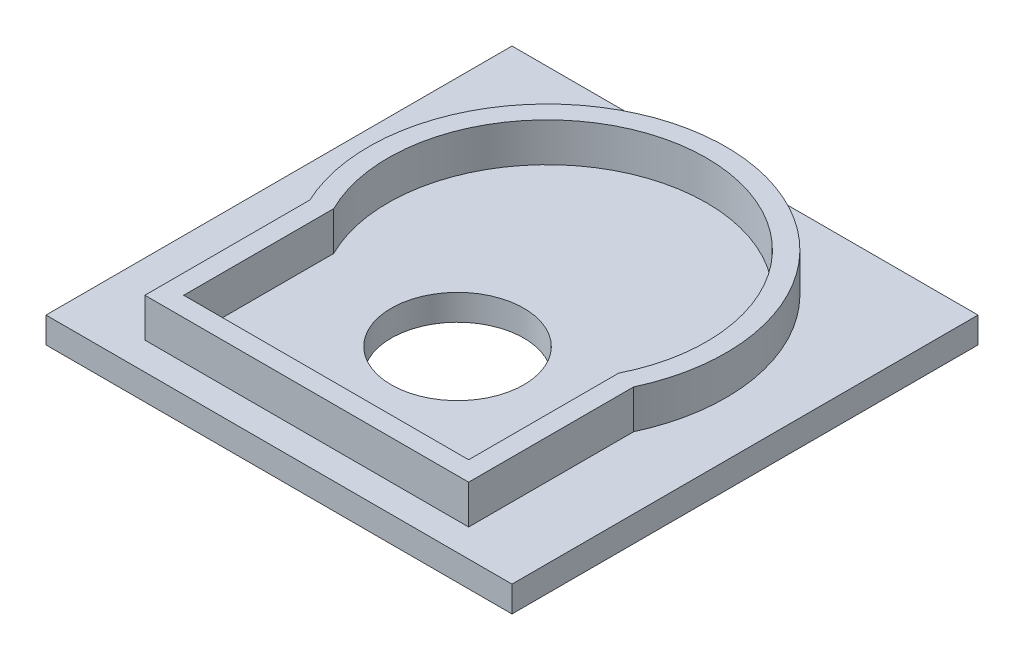
SolidWorks part; units mm, degrees
ref_plane "Front Plane" through (0, 0, 0) normal (0, 0, 1) x (1, 0, 0)
ref_plane "Top Plane" through (0, 0, 0) normal (0, 1, 0) x (1, 0, 0)
ref_plane "Right Plane" through (0, 0, 0) normal (1, 0, 0) x (0, 0, -1)
sketch "Sketch1" plane through (0, 0, 0) normal (0, 1, 0) x (1, 0, 0)
  line L1 (-76.2, 76.2) -> (76.2, 76.2)
  line L2 (-76.2, 76.2) -> (-76.2, -76.2)
  line L3 (-76.2, -76.2) -> (76.2, -76.2)
  line L4 (76.2, 76.2) -> (76.2, -76.2)
  line L5 (-76.2, 76.2) -> (76.2, -76.2) construction
  line L6 (-76.2, -76.2) -> (76.2, 76.2) construction
  point P0 (0, 0)
  dimension "D1" = 152.4
  dimension "D2" = 152.4
extrude "Boss-Extrude1" add sketch "Sketch1" along normal blind 8.4667
sketch "Sketch2" plane through (0, 0, 0) normal (0, -1, 0) x (-1, 0, 0)
  line L0 (-61.7294, 44.45) -> (0, -61.1273) construction
  line L1 (0, -61.1273) -> (61.346, 44.6733) construction
  line L2 (61.346, 44.6733) -> (-61.7294, 44.45) construction
  line L3 (-76.2, 76.2) -> (76.2, 76.2) construction
  line L4 (0, 0) -> (0, -122.2547) construction
  circle A0 centre (61.346, 44.6733) radius 5.08
  circle A1 centre (0, -61.1273) radius 5.08
  circle A2 centre (-61.7294, 44.45) radius 5.08
  point P10 (-0.1284, 9.6324)
  dimension "D2" = 10.16
  dimension "D3" = 123.0754
  dimension "D4" = 105.5773
  dimension "D5" = 105.8006
  dimension "D6" = 31.75
  dimension "D1" = 3
extrude "Cut-Extrude1" cut sketch "Sketch2" against normal blind 6.35 contours A2 | A0 | A1
sketch "Sketch3" plane through (0, 8.4667, 0) normal (0, 1, 0) x (1, 0, 0)
  line L0 (-52.9406, -13.16) -> (-52.9406, -67.1216)
  line L1 (-52.9406, -67.1216) -> (52.9406, -67.1216)
  line L2 (52.9406, -13.16) -> (52.9406, -67.1216)
  line L4 (-46.5906, -11.7088) -> (-46.5906, -60.7716)
  line L5 (-46.5906, -60.7716) -> (46.5906, -60.7716)
  line L6 (46.5906, -11.7088) -> (46.5906, -60.7716)
  arc A1 (46.5906, -11.7088) -> (-46.5906, -11.7088) centre (0, 11.542) ccw
  arc A2 (52.9406, -13.16) -> (-52.9406, -13.16) centre (0, 11.542) ccw
  dimension "D1" = 6.35
extrude "Boss-Extrude3" add sketch "Sketch3" along normal blind 12.7
sketch "Sketch4" plane through (0, 8.4667, 0) normal (0, 1, 0) x (1, 0, 0)
  line L0 (0, 0) -> (0, -17.8135)
  circle A0 centre (0, -17.8135) radius 21.6974
extrude "Cut-Extrude2" cut sketch "Sketch4" against normal blind 12.7
